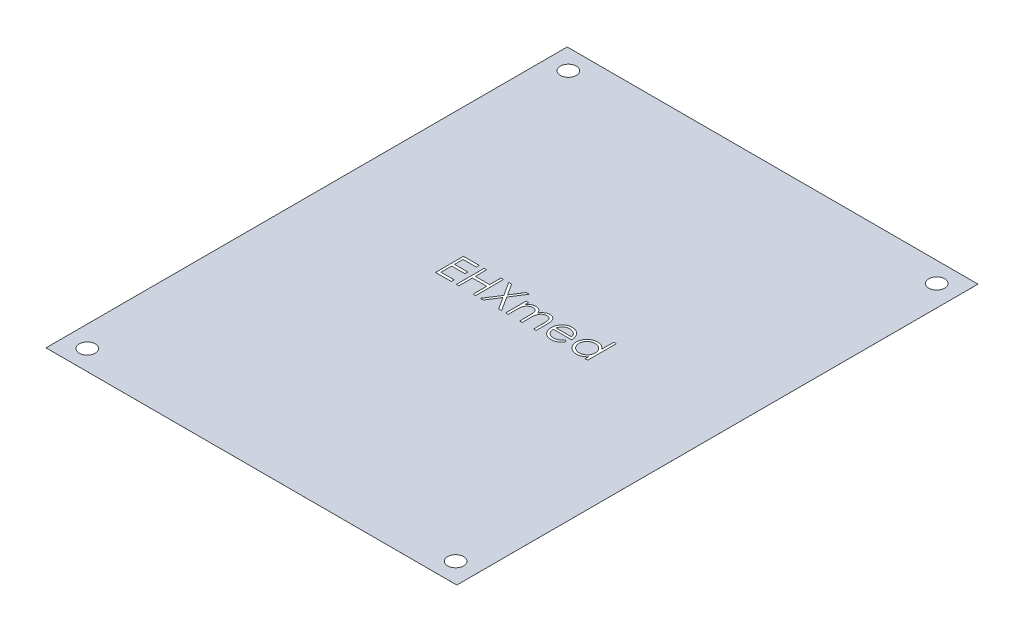
SolidWorks part; units mm, degrees
ref_plane "Front Plane" through (0, 0, 0) normal (0, 0, 1) x (1, 0, 0)
ref_plane "Top Plane" through (0, 0, 0) normal (0, 1, 0) x (1, 0, 0)
ref_plane "Right Plane" through (0, 0, 0) normal (1, 0, 0) x (0, 0, -1)
sketch "Sketch2" plane through (0, 0, 0) normal (0, 1, 0) x (1, 0, 0)
  line L1 (-46.736, -59.2899) -> (46.736, -59.2899)
  line L2 (-46.736, -59.2899) -> (-46.736, 59.2899)
  line L3 (-46.736, 59.2899) -> (46.736, 59.2899)
  line L4 (46.736, -59.2899) -> (46.736, 59.2899)
  line L5 (-46.736, -59.2899) -> (46.736, 59.2899) construction
  line L6 (-46.736, 59.2899) -> (46.736, -59.2899) construction
  point P0 (0, 0)
  dimension "D1" = 118.5799
  dimension "D2" = 93.472
extrude "Boss-Extrude1" add sketch "Sketch2" along normal blind 0.0025
sketch "Sketch3" plane through (0, 0.0025, 0) normal (0, 1, 0) x (1, 0, 0)
  line L1 (-41.91, -54.737) -> (41.91, -54.737)
  line L2 (-41.91, -54.737) -> (-41.91, 54.737)
  line L3 (-41.91, 54.737) -> (41.91, 54.737)
  line L4 (41.91, -54.737) -> (41.91, 54.737)
  line L5 (-41.91, -54.737) -> (41.91, 54.737) construction
  line L6 (-41.91, 54.737) -> (41.91, -54.737) construction
  circle A0 centre (-41.91, 54.737) radius 1.8288
  circle A7 centre (41.91, 54.737) radius 1.8288
  circle A8 centre (41.91, -54.737) radius 1.8288
  circle A9 centre (-41.91, -54.737) radius 1.8288
  point P0 (0, 0)
  dimension "D3" = 3.6576
  dimension "D1" = 109.474
  dimension "D2" = 83.82
  dimension "D4" = 2
  dimension "D5" = 2
extrude "Cut-Extrude1" cut sketch "Sketch3" against normal through all contours A9 | A8 | A7 | A0
sketch "Sketch5" plane through (0, 0.0025, 0) normal (0, 1, 0) x (1, 0, 0)
  text T0 "EHXmed\r\n" font "Century Gothic" height 6.35
extrude "Cut-Extrude2" cut sketch "Sketch5" against normal blind 2.54
